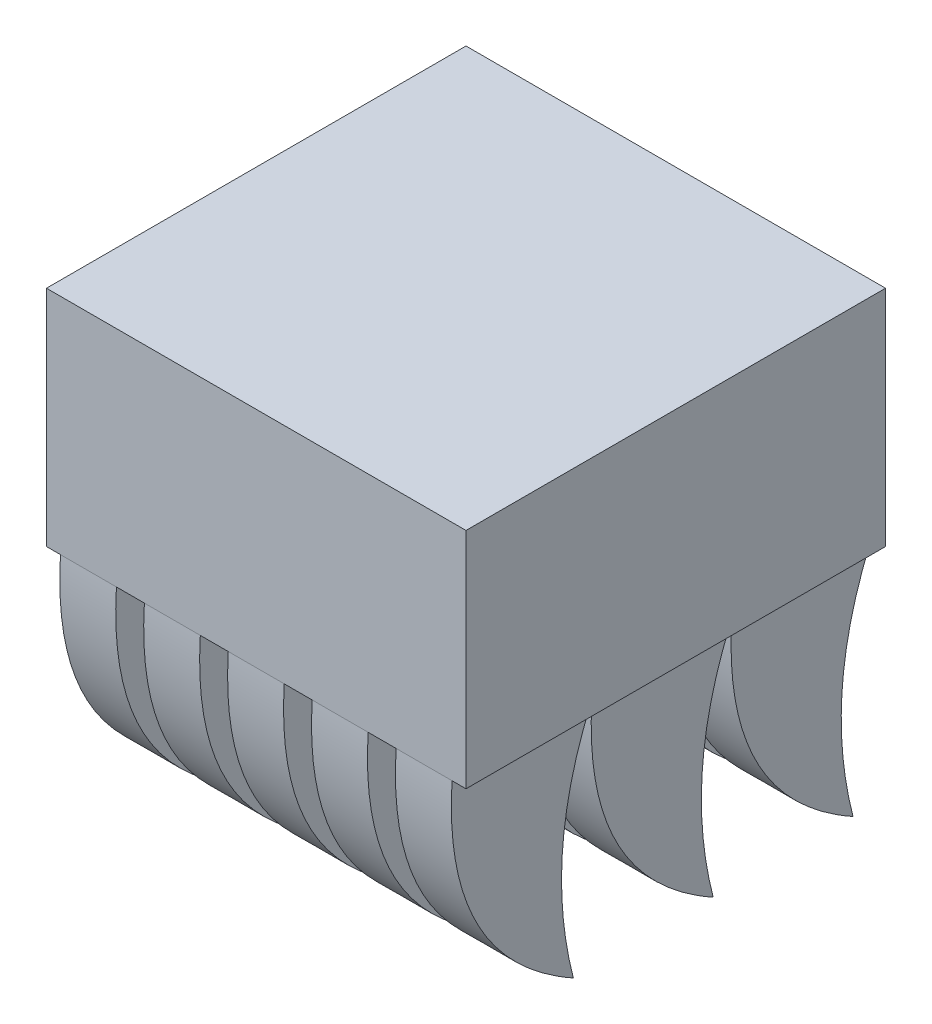
SolidWorks part; units mm, degrees
ref_plane "정면" through (0, 0, 0) normal (0, 0, 1) x (1, 0, 0)
ref_plane "윗면" through (0, 0, 0) normal (0, 1, 0) x (1, 0, 0)
ref_plane "우측면" through (0, 0, 0) normal (1, 0, 0) x (0, 0, -1)
sketch "스케치1" plane through (0, 0, 0) normal (0, 1, 0) x (1, 0, 0)
  line L1 (-7.5, -7.5) -> (7.5, -7.5)
  line L2 (-7.5, -7.5) -> (-7.5, 7.5)
  line L3 (-7.5, 7.5) -> (7.5, 7.5)
  line L4 (7.5, -7.5) -> (7.5, 7.5)
  line L5 (-7.5, -7.5) -> (7.5, 7.5) construction
  line L6 (-7.5, 7.5) -> (7.5, -7.5) construction
  point P0 (0, 0)
  dimension "D1" = 15
  dimension "D2" = 15
extrude "보스-돌출1" add sketch "스케치1" along normal mid plane 8
sketch "스케치3" plane through (0, 0, 0) normal (1, 0, 0) x (0, 0, -1)
  line L4 (2.5, -4) -> (7.5, -4)
  spline S0 degree 2 poles (2.5, -4) (2.1528, -9.6643) (6.8379, -12.2781) knots 0 0 0 1 1 1
  spline S1 degree 2 poles (6.8379, -12.2781) (5.7394, -8.0097) (7.5, -4) knots 0 0 0 1 1 1
  dimension "D1" = 5
extrude "보스-돌출2" add sketch "스케치3" along normal mid plane 2
sketch "스케치5" plane through (0, -4, 0) normal (0, -1, 0) x (1, 0, 0)
  line L0 (1, -7.5) -> (1, -2.5) construction
  line L1 (1, -2.5) -> (-1, -2.5) construction
  line L2 (-7.5, 7.5) -> (7.5, 7.5) construction
  line L3 (-7.5, -7.5) -> (-7.5, 7.5) construction
  line L4 (7.5, 7.5) -> (7.5, -7.5) construction
  point P0 (0, -5)
  point P3 (1, -5)
  point P6 (0, -2.5)
  point P7 (-5, 4.84)
  point P8 (5, 4.84)
  dimension "D1" = 2.66
  dimension "D2" = 2.5
  dimension "D3" = 2.5
  dimension "D4" = 2.66
pattern_sketch "스케치 패턴2" [suppressed]
pattern_linear "선형 패턴1" count 3 spacing 3 along (-1, 0, 0) count 3 spacing 5 along (0, 0, 1) of "보스-돌출2"
pattern_linear "선형 패턴2" count 3 spacing 3 along (-1, 0, 0) count 3 spacing 5 along (0, 0, -1) of "보스-돌출2"
